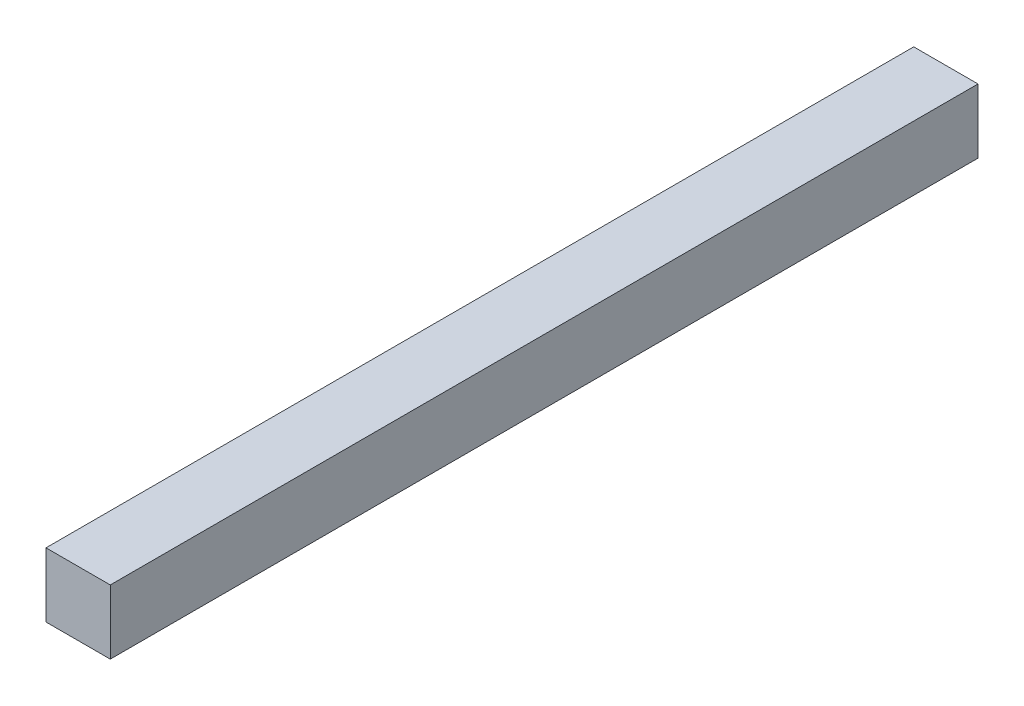
SolidWorks part; units mm, degrees
ref_plane "Front" through (0, 0, 0) normal (0, 0, 1) x (1, 0, 0)
ref_plane "Top" through (0, 0, 0) normal (0, 1, 0) x (1, 0, 0)
ref_plane "Right" through (0, 0, 0) normal (1, 0, 0) x (0, 0, -1)
sketch "Sketch1" plane through (0, 0, 0) normal (0, 0, 1) x (1, 0, 0)
  line L1 (0, 0) -> (-2.54, 0)
  line L2 (0, 0) -> (0, 2.54)
  line L3 (0, 2.54) -> (-2.54, 2.54)
  line L4 (-2.54, 0) -> (-2.54, 2.54)
  dimension "D1" = 2.54
  dimension "D2" = 2.54
extrude "Boss-Extrude1" add sketch "Sketch1" along normal blind 34.29
sketch "Sketch2" plane through (-2.54, 0, 0) normal (-1, 0, 0) x (0, 0, 1)
  line L0 (34.29, 2.54) -> (34.29, 0) construction
  line L1 (34.29, 0) -> (0, 0) construction
  circle A0 centre (33.02, 1.27) radius 0.4445
  point P2 (0, 0)
  dimension "D1" = 0.889
  dimension "D2" = 1.27
  dimension "D3" = 1.27
